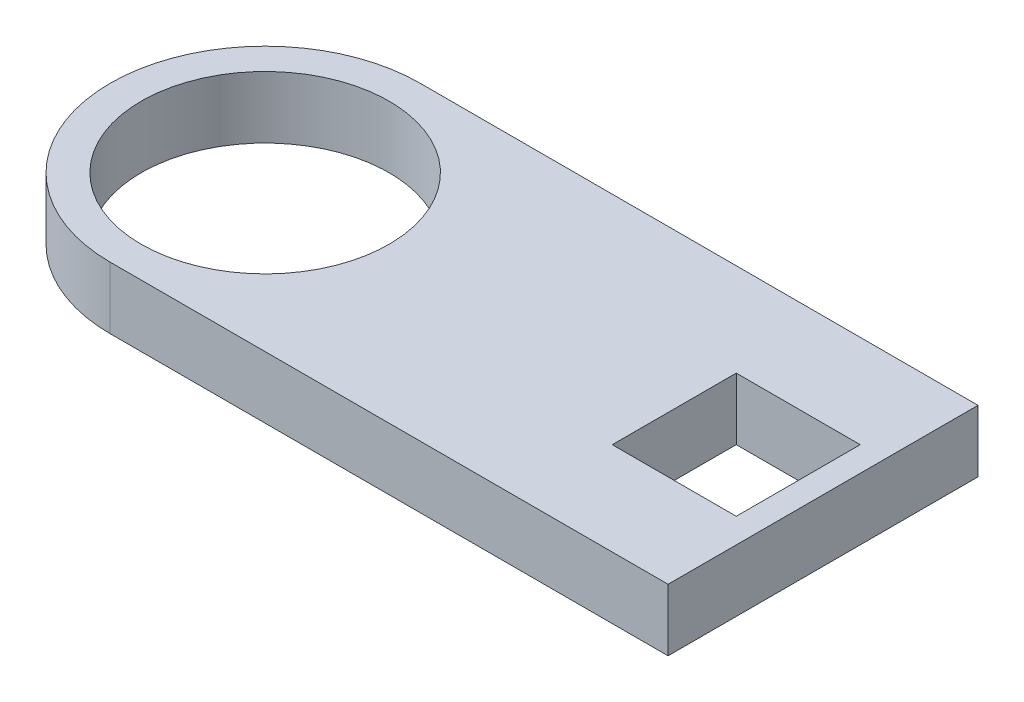
SolidWorks part; units mm, degrees
ref_plane "Front Plane" through (0, 0, 0) normal (0, 0, 1) x (1, 0, 0)
ref_plane "Top Plane" through (0, 0, 0) normal (0, 1, 0) x (1, 0, 0)
ref_plane "Right Plane" through (0, 0, 0) normal (1, 0, 0) x (0, 0, -1)
sketch "Sketch1" plane through (0, 0, 0) normal (0, 1, 0) x (1, 0, 0)
  line L1 (0, 0) -> (45, 0)
  line L3 (0, 25) -> (45, 25)
  line L4 (45, 0) -> (45, 25)
  line L5 (43, 17.5) -> (33, 17.5)
  line L6 (43, 17.5) -> (43, 7.5)
  line L7 (43, 7.5) -> (33, 7.5)
  line L8 (33, 17.5) -> (33, 7.5)
  arc A0 (0, 25) -> (0, 0) centre (0, 12.5) ccw
  circle A1 centre (0, 12.5) radius 10
  dimension "D3" = 20
  dimension "D1" = 45
  dimension "D2" = 25
  dimension "D4" = 10
  dimension "D5" = 7.5
  dimension "D6" = 2
extrude "Boss-Extrude1" add sketch "Sketch1" along normal blind 5
